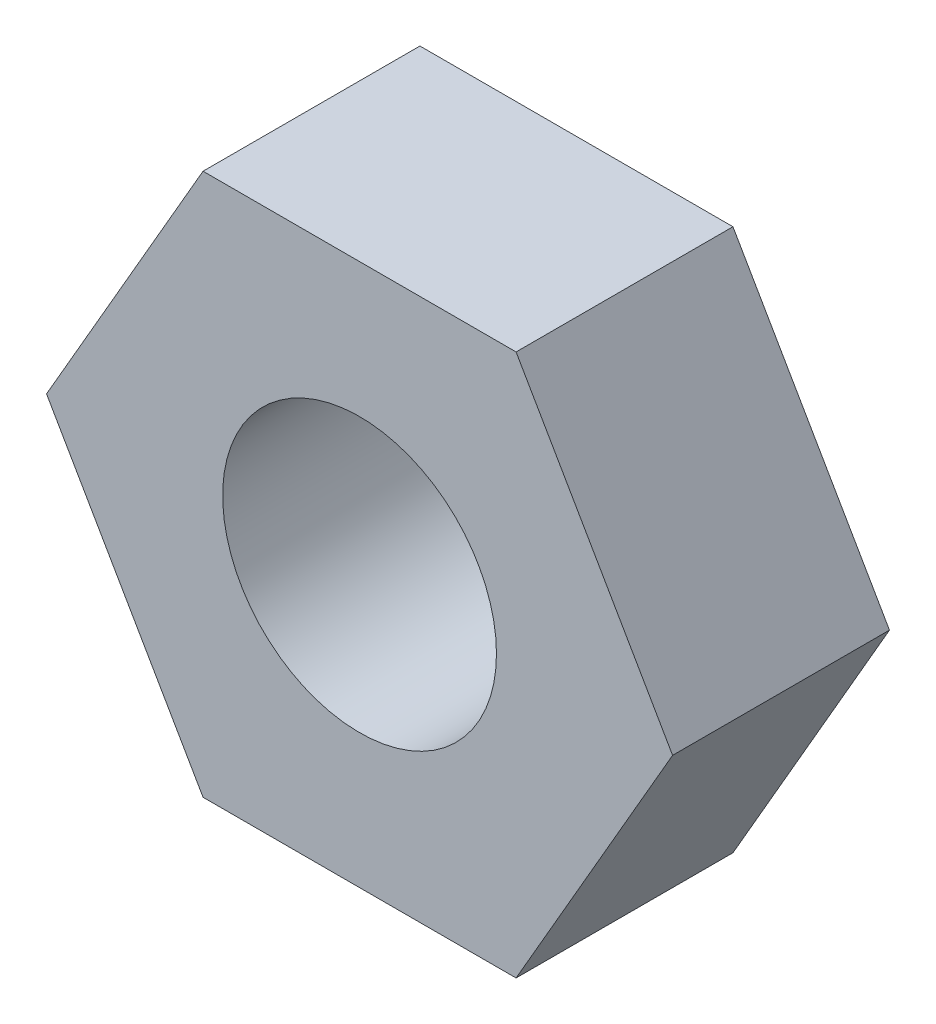
SolidWorks part; units mm, degrees
ref_plane "前视基准面" through (0, 0, 0) normal (0, 0, 1) x (1, 0, 0)
ref_plane "上视基准面" through (0, 0, 0) normal (0, 1, 0) x (1, 0, 0)
ref_plane "右视基准面" through (0, 0, 0) normal (1, 0, 0) x (0, 0, -1)
other "Configuration Table"
sketch "ISO4032_M2_AF4_h1p6_Sketch" plane through (0, 0, 0) normal (0, 0, 1) x (1, 0, 0)
  line L0 (2.3094, 0) -> (1.1547, 2)
  line L1 (1.1547, 2) -> (-1.1547, 2)
  line L2 (-1.1547, 2) -> (-2.3094, 0)
  line L3 (-2.3094, 0) -> (-1.1547, -2)
  line L4 (-1.1547, -2) -> (1.1547, -2)
  line L5 (1.1547, -2) -> (2.3094, 0)
  circle A0 centre (0, 0) radius 1.01
extrude "ISO4032_M2_AF4_h1p6" add sketch "ISO4032_M2_AF4_h1p6_Sketch" along normal blind 1.6 separate body
